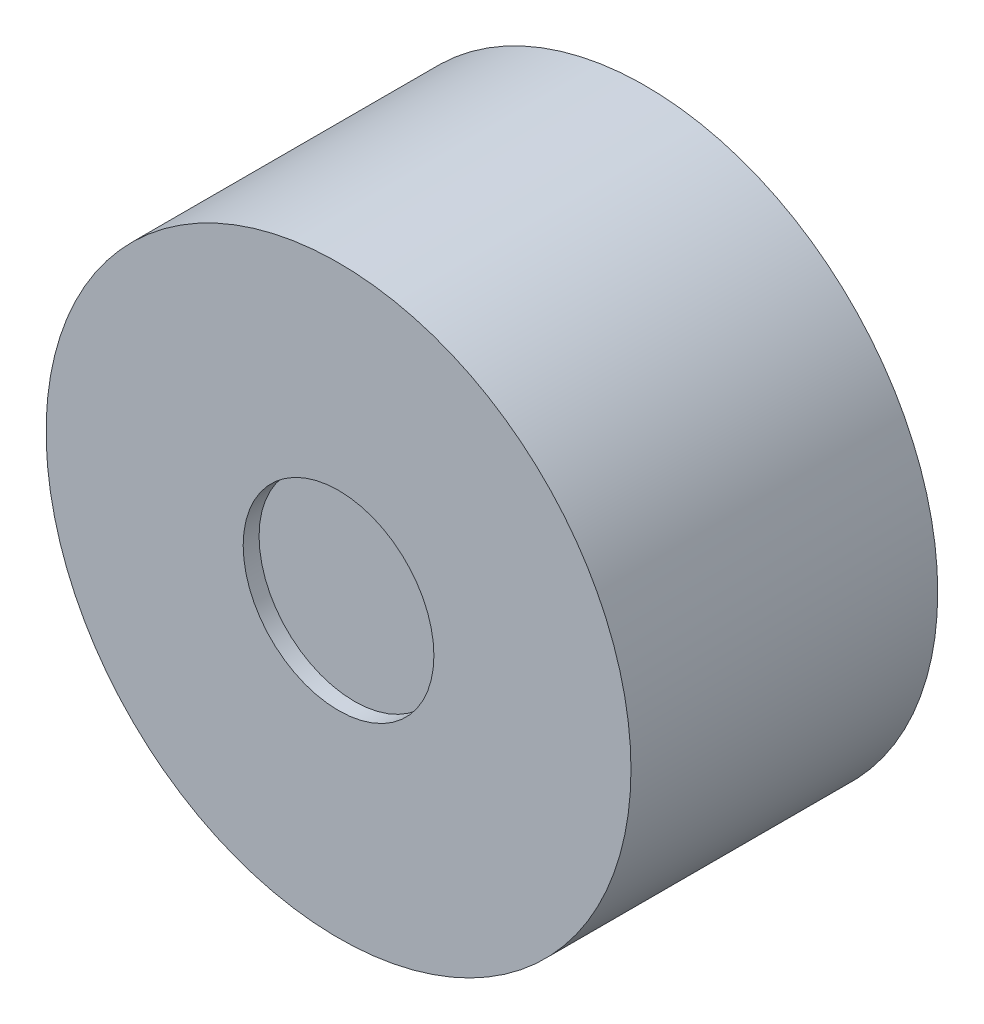
SolidWorks part; units mm, degrees
ref_plane "Alzado" through (0, 0, 0) normal (0, 0, 1) x (1, 0, 0)
ref_plane "Planta" through (0, 0, 0) normal (0, 1, 0) x (1, 0, 0)
ref_plane "Vista lateral" through (0, 0, 0) normal (1, 0, 0) x (0, 0, -1)
sketch "Croquis1" plane through (0, 0, 0) normal (0, 0, 1) x (1, 0, 0)
  circle A0 centre (0, 0) radius 18.4
  dimension "D1" = 36.8
extrude "Saliente-Extruir1" add sketch "Croquis1" along normal blind 24.3
sketch "Croquis2" plane through (0, 0, 24.3) normal (0, 0, 1) x (1, 0, 0)
  circle A0 centre (0, 0) radius 3
  circle A1 centre (0, 0) radius 9.5 construction
  circle A2 centre (0, 9.5) radius 1.25
  circle A3 centre (9.5, 0) radius 1.25
  circle A4 centre (0, -9.5) radius 1.25
  circle A5 centre (-9.5, 0) radius 1.25
  point P15 (0, 0)
  dimension "D1" = 6
  dimension "D2" = 19
  dimension "D3" = 2.5
  dimension "D4" = 4
extrude "Cortar-Extruir1" cut sketch "Croquis2" against normal blind 5
sketch "Croquis3" plane through (0, 0, 0) normal (0, 0, -1) x (-1, 0, 0)
  circle A0 centre (0, 0) radius 9.5 construction
  circle A1 centre (-9.5, 0) radius 1.25
  circle A2 centre (0, 9.5) radius 1.25
  circle A3 centre (9.5, 0) radius 1.25
  circle A4 centre (0, -9.5) radius 1.25
  circle A5 centre (0, 0) radius 5
  point P14 (0, 0)
  dimension "D1" = 19
  dimension "D2" = 2.5
  dimension "D3" = 4
extrude "Cortar-Extruir2" cut sketch "Croquis3" against normal blind 5
sketch "Croquis6" plane through (0, 0, 24.3) normal (0, 0, 1) x (1, 0, 0)
  circle A0 centre (0, 0) radius 18.4
extrude "Cortar-Extruir3" cut sketch "Croquis6" against normal blind 5
sketch "Croquis7" plane through (0, 0, 19.3) normal (0, 0, 1) x (1, 0, 0)
  circle A0 centre (0, 0) radius 6
extrude "Cortar-Extruir4" cut sketch "Croquis7" against normal blind 1
